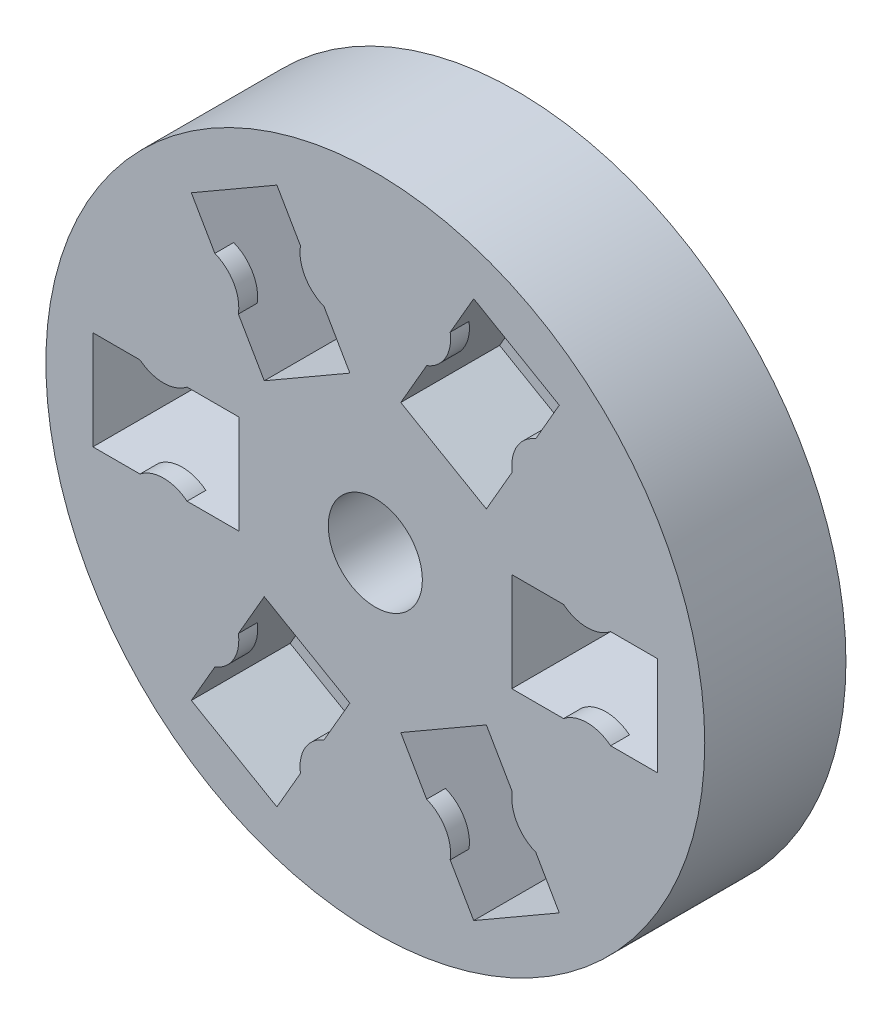
SolidWorks part; units mm, degrees
ref_plane "Front Plane" through (0, 0, 0) normal (0, 0, 1) x (1, 0, 0)
ref_plane "Top Plane" through (0, 0, 0) normal (0, 1, 0) x (1, 0, 0)
ref_plane "Right Plane" through (0, 0, 0) normal (1, 0, 0) x (0, 0, -1)
sketch "Sketch1" plane through (0, 0, 0) normal (0, 0, 1) x (1, 0, 0)
  circle A0 centre (-9.5, 0) radius 7
  circle A2 centre (-9.5, 0) radius 1
  dimension "D1" = 6
extrude "Boss-Extrude1" add sketch "Sketch1" against normal blind 3
sketch "Sketch2" plane through (0, 0, 0) normal (0, 0, 1) x (1, 0, 0)
  line L0 (-16.5, 0) -> (-9.5, 0) construction
  line L1 (-9.5, 0) -> (-9.5, 7) construction
  line L3 (-15.5, -1.05) -> (-12.4, -1.05)
  line L4 (-15.5, -1.05) -> (-15.5, 1.05)
  line L5 (-15.5, 1.05) -> (-12.4, 1.05)
  line L6 (-12.4, -1.05) -> (-12.4, 1.05)
  line L7 (-15.5, -1.05) -> (-12.4, 1.05) construction
  line L8 (-15.5, 1.05) -> (-12.4, -1.05) construction
  circle A0 centre (-9.5, 0) radius 7 construction
  circle A2 centre (-9.5, 0) radius 1 construction
  point P5 (-13.95, 0)
  dimension "D1" = 2.1
  dimension "D2" = 3.1
  dimension "D3" = 1.9
extrude "Cut-Extrude1" cut sketch "Sketch2" against normal blind 2.1
pattern_circular "CirPattern1" count 6 over 360 about axis through (-9.5, 0, 0) along (0, 0, 1) of "Cut-Extrude1"
sketch "Sketch3" plane through (0, 0, 0) normal (0, 0, 1) x (1, 0, 0)
  line L0 (-15.5, -1.05) -> (-12.4, -1.05) construction
  line L1 (-14.5, -1.05) -> (-13.5, -1.05)
  line L2 (-15.5, 1.05) -> (-15.5, -1.05) construction
  line L3 (-15.5, 0) -> (-12.4, 0) construction
  line L4 (-12.4, -1.05) -> (-12.4, 1.05) construction
  line L5 (-14.5, 1.05) -> (-13.5, 1.05)
  arc A0 (-14.5, -1.05) -> (-13.5, -1.05) centre (-14, -1.6745) cw
  arc A1 (-14.5, 1.05) -> (-13.5, 1.05) centre (-14, 1.6745) ccw
  dimension "D1" = 1
  dimension "D3" = 0.8
  dimension "D2" = 1
extrude "Boss-Extrude2" add sketch "Sketch3" against normal blind 0.4
pattern_circular "CirPattern2" count 6 over 360 about axis through (-9.5, 0, 0) along (0, 0, 1) of "Boss-Extrude2"
